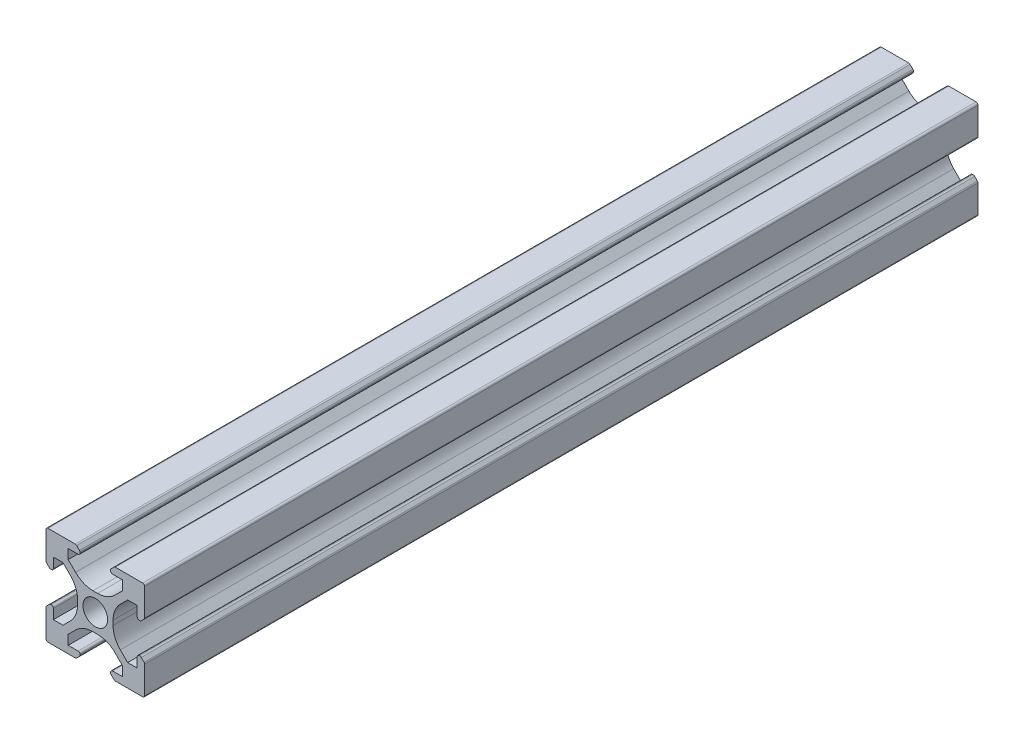
SolidWorks part; units mm, degrees
material "6063-T83"
ref_plane "Plano frontal" through (0, 0, 0) normal (0, 0, 1) x (1, 0, 0)
ref_plane "Plano superior" through (0, 0, 0) normal (0, 1, 0) x (1, 0, 0)
ref_plane "Plano direito" through (0, 0, 0) normal (1, 0, 0) x (0, 0, -1)
sketch "Esboço1" plane through (0, 0, 0) normal (0, 0, 1) x (1, 0, 0)
  line L0 (-9.0343, 3.1) -> (-8.9, 3.1)
  line L3 (-10, 10) -> (-4.0657, 10)
  line L5 (-10, -10) -> (10, 10) construction
  line L6 (-10, 10) -> (10, -10) construction
  line L7 (-8.5, 3.5) -> (-8.5, 5.5)
  line L8 (-10, 0) -> (10, 0) construction
  line L9 (0, 10) -> (0, -10) construction
  line L12 (-8.5, 5.5) -> (-6.5607, 5.5)
  line L15 (-6.5607, 5.5) -> (-5.0645, 4.0038)
  line L16 (-3.6, 0.4683) -> (-3.6, 0)
  line L17 (-0.4683, 3.6) -> (0, 3.6)
  line L18 (-5.5, 6.5607) -> (-4.0038, 5.0645)
  line L21 (-5.5, 8.5) -> (-5.5, 6.5607)
  line L24 (-3.5, 8.5) -> (-5.5, 8.5)
  line L25 (-3.1, 9.0343) -> (-3.1, 8.9)
  line L44 (-10, 4.0657) -> (-10, 10)
  line L45 (-9.8828, 3.7828) -> (-9.3172, 3.2172)
  line L46 (-3.7828, 9.8828) -> (-3.2172, 9.3172)
  line L47 (-3.6, 0) -> (-2.5, 0)
  line L48 (0, 3.6) -> (0, 2.5)
  arc A0 (-3.5, 8.5) -> (-3.1, 8.9) centre (-3.5, 8.9) ccw
  arc A1 (-3.7828, 9.8828) -> (-4.0657, 10) centre (-4.0657, 9.6) ccw
  arc A2 (-10, 4.0657) -> (-9.8828, 3.7828) centre (-9.6, 4.0657) ccw
  arc A3 (-8.5, 3.5) -> (-8.9, 3.1) centre (-8.9, 3.5) cw
  arc A4 (-3.2172, 9.3172) -> (-3.1, 9.0343) centre (-3.5, 9.0343) cw
  arc A5 (-9.3172, 3.2172) -> (-9.0343, 3.1) centre (-9.0343, 3.5) ccw
  arc A6 (-3.6, 0.4683) -> (-5.0645, 4.0038) centre (-8.6, 0.4683) ccw
  arc A7 (-4.0038, 5.0645) -> (-0.4683, 3.6) centre (-0.4683, 8.6) ccw
  circle A8 centre (0, 0) radius 2.5
  point P6 (-10, 3.1)
  point P28 (-3.1, 8.5)
  point P31 (-3.1, 10)
  point P33 (-3.9, 10)
  point P36 (-10, 3.9)
  point P39 (-8.5, 3.1)
  point P42 (-3.1, 9.2)
  point P45 (-9.2, 3.1)
  point P48 (-3.6, 2.5393)
  point P51 (-2.5393, 3.6)
  dimension "D5" = 10
  dimension "D9" = 0.4
  dimension "D10" = 0.4
  dimension "D11" = 5
  dimension "D12" = 5
  dimension "D13" = 5
  dimension "D1" = 6.9
  dimension "D2" = 1.5
  dimension "D3" = 3.6
  dimension "D4" = 1.5
  dimension "D6" = 2.4
  dimension "D7" = 3.6
  dimension "D8" = 45
extrude "Ressalto-extrusão1" add sketch "Esboço1" along normal blind 169
sketch "Esboço3" plane through (0, 0, 0) normal (1, 0, 0) x (0, 0, -1)
  line L0 (0, 0) -> (-169, 0) construction
  line L1 (-169, 2.5) -> (-169, 0) construction
pattern_circular "PadrãoCircular1" count 4 every 90 about axis through (0, 0, 0) along (0, 0, 1) of "Ressalto-extrusão1"
fillet "Filete1" radius 0.4 4 edges at (-10, -10, 84.5) (-10, 10, 84.5) (10, -10, 84.5) (10, 10, 84.5)
